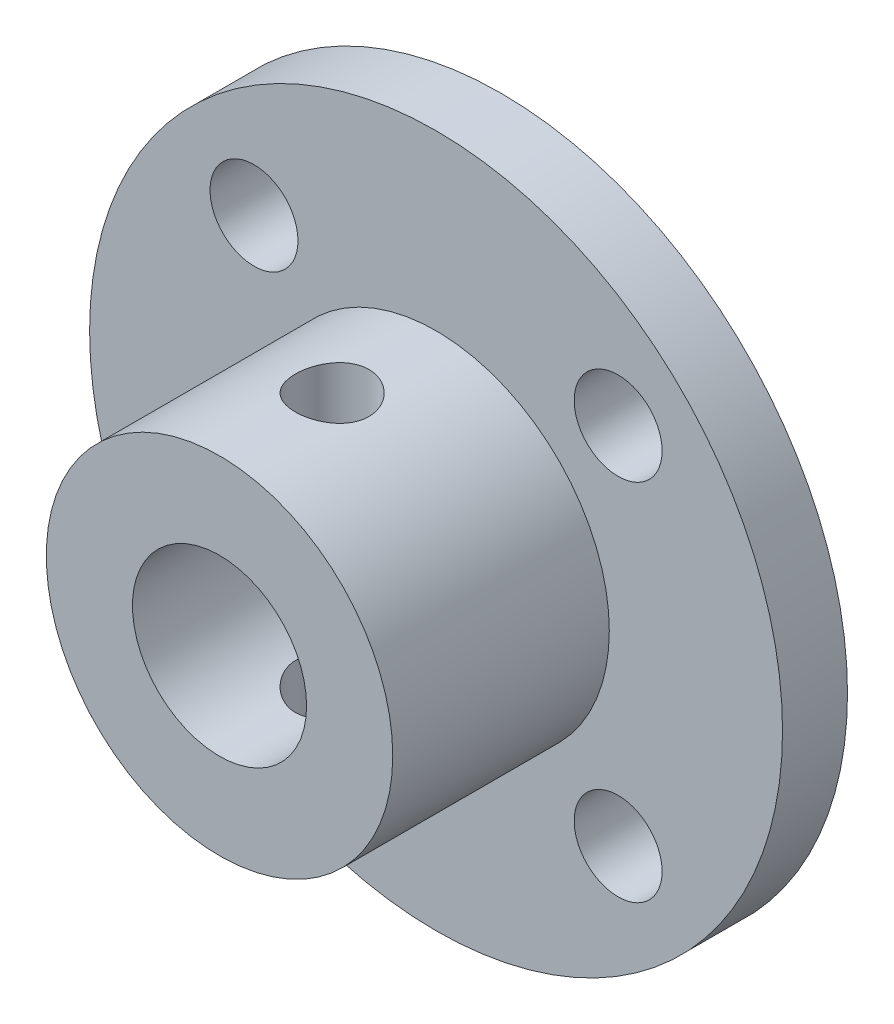
SolidWorks part; units mm, degrees
ref_plane "Plan de face" through (0, 0, 0) normal (0, 0, 1) x (1, 0, 0)
ref_plane "Plan de dessus" through (0, 0, 0) normal (0, 1, 0) x (1, 0, 0)
ref_plane "Plan de droite" through (0, 0, 0) normal (1, 0, 0) x (0, 0, -1)
sketch "Esquisse1" plane through (0, 0, 0) normal (0, 0, 1) x (1, 0, 0)
  line L0 (0, 0) -> (-11.3137, 11.3137) construction
  line L1 (0, 0) -> (11.3137, -11.3137) construction
  line L2 (0, 0) -> (11.3137, 11.3137) construction
  line L3 (0, 0) -> (-11.3137, -11.3137) construction
  line L4 (0, 0) -> (-15.1034, 0) construction
  line L5 (55, 0) -> (-55, 0) construction
  circle A0 centre (0, 0) radius 16
  circle A1 centre (-8.4075, 8.4075) radius 2.03
  circle A2 centre (8.4075, 8.4075) radius 2.03
  circle A3 centre (8.4075, -8.4075) radius 2.03
  circle A4 centre (-8.4075, -8.4075) radius 2.03
  dimension "D1" = 32
  dimension "D2" = 4.06
  dimension "D3" = 4.06
  dimension "D4" = 4.06
  dimension "D5" = 4.06
  dimension "D6" = 11.89
  dimension "D7" = 11.89
  dimension "D8" = 11.89
  dimension "D9" = 11.89
  dimension "D10" = 45
extrude "Boss.-Extru.1" add sketch "Esquisse1" along normal blind 3
sketch "Esquisse2" plane through (0, 0, 3) normal (0, 0, 1) x (1, 0, 0)
  circle A0 centre (0, 0) radius 8
  circle A1 centre (0, 0) radius 4.02
  dimension "D1" = 16
  dimension "D2" = 8.04
extrude "Boss.-Extru.2" add sketch "Esquisse2" along normal blind 10
sketch "Esquisse3" plane through (0, 0, 13) normal (0, 0, 1) x (1, 0, 0)
  circle A0 centre (0, 0) radius 4.02
extrude "Enlèv. mat.-Extru.1" cut sketch "Esquisse3" against normal through all
sketch "Esquisse4" plane through (0, 0, 0) normal (0, 1, 0) x (1, 0, 0)
  line L0 (0, 0) -> (0, -13) construction
  line L1 (-8, -13) -> (8, -13) construction
  circle A0 centre (0, -7.8) radius 1.7
  dimension "D1" = 3.4
  dimension "D2" = 5.2
extrude "Enlèv. mat.-Extru.2" cut sketch "Esquisse4" against normal through all and the other way through all
